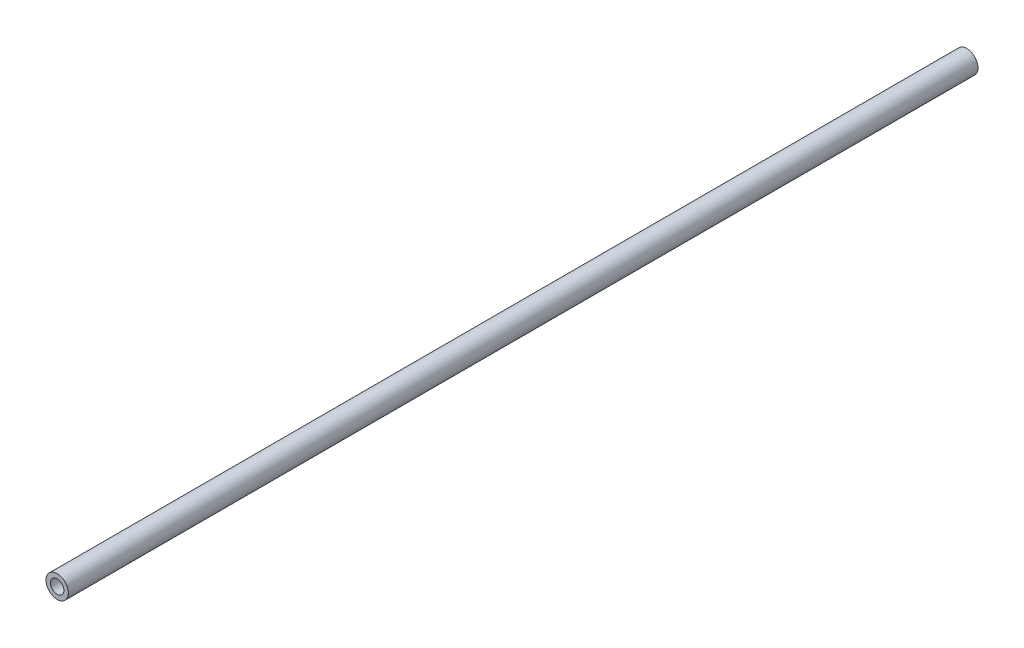
SolidWorks part; units mm, degrees
material "Silicon Rubber"
ref_plane "Front Plane" through (0, 0, 0) normal (0, 0, 1) x (1, 0, 0)
ref_plane "Top Plane" through (0, 0, 0) normal (0, 1, 0) x (1, 0, 0)
ref_plane "Right Plane" through (0, 0, 0) normal (1, 0, 0) x (0, 0, -1)
sketch "Sketch1" plane through (0, 0, 0) normal (0, 0, 1) x (1, 0, 0)
  circle A0 centre (0, 0) radius 1.5
  circle A1 centre (0, 0) radius 2.5
  dimension "D1" = 3
  dimension "D2" = 5
extrude "Boss-Extrude1" add sketch "Sketch1" along normal blind 203.2
